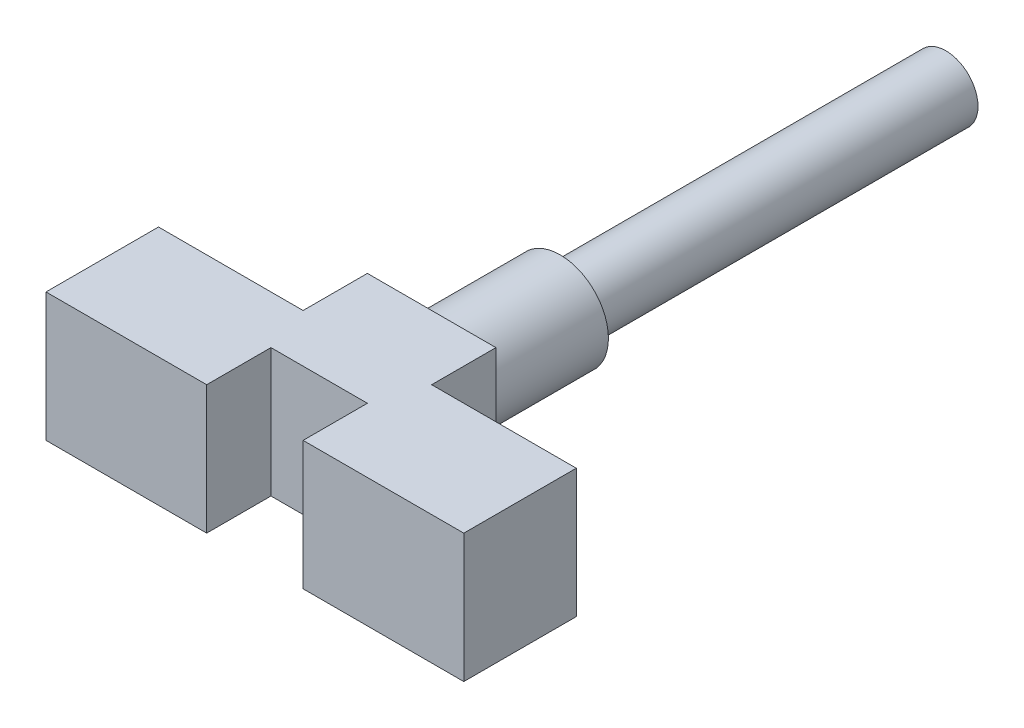
SolidWorks part; units mm, degrees
ref_plane "Front Plane" through (0, 0, 0) normal (0, 0, 1) x (1, 0, 0)
ref_plane "Top Plane" through (0, 0, 0) normal (0, 1, 0) x (1, 0, 0)
ref_plane "Right Plane" through (0, 0, 0) normal (1, 0, 0) x (0, 0, -1)
sketch "Sketch1" plane through (0, 0, 0) normal (0, 1, 0) x (1, 0, 0)
  line L0 (12.7, 12.7) -> (-12.7, 12.7)
  line L1 (-12.7, 12.7) -> (-12.7, 0)
  line L2 (-12.7, 0) -> (-41.275, 0)
  line L3 (-41.275, 0) -> (-41.275, -22.225)
  line L4 (-41.275, -22.225) -> (-9.525, -22.225)
  line L5 (-9.525, -22.225) -> (-9.525, -9.525)
  line L6 (-9.525, -9.525) -> (9.525, -9.525)
  line L7 (9.525, -9.525) -> (9.525, -22.225)
  line L8 (9.525, -22.225) -> (41.275, -22.225)
  line L9 (41.275, -22.225) -> (41.275, 0)
  line L10 (41.275, 0) -> (12.7, 0)
  line L11 (12.7, 0) -> (12.7, 12.7)
  line L12 (0, -9.525) -> (0, 0) construction
  dimension "D1" = 25.4
  dimension "D2" = 31.75
  dimension "D3" = 9.525
  dimension "D4" = 12.7
  dimension "D5" = 12.7
  dimension "D6" = 19.05
extrude "Boss-Extrude1" add sketch "Sketch1" along normal mid plane 25.4
sketch "Sketch2" plane through (0, 0, -12.7) normal (0, 0, -1) x (-1, 0, 0)
  line L0 (-12.7, 12.7) -> (12.7, -12.7) construction
  circle A0 centre (0, 0) radius 9.525
  dimension "D1" = 19.05
extrude "Boss-Extrude2" add sketch "Sketch2" along normal blind 25.4
sketch "Sketch3" plane through (0, 0, -38.1) normal (0, 0, -1) x (-1, 0, 0)
  circle A0 centre (0, 0) radius 6.35
  dimension "D1" = 12.7
extrude "Boss-Extrude3" add sketch "Sketch3" along normal blind 76.2
